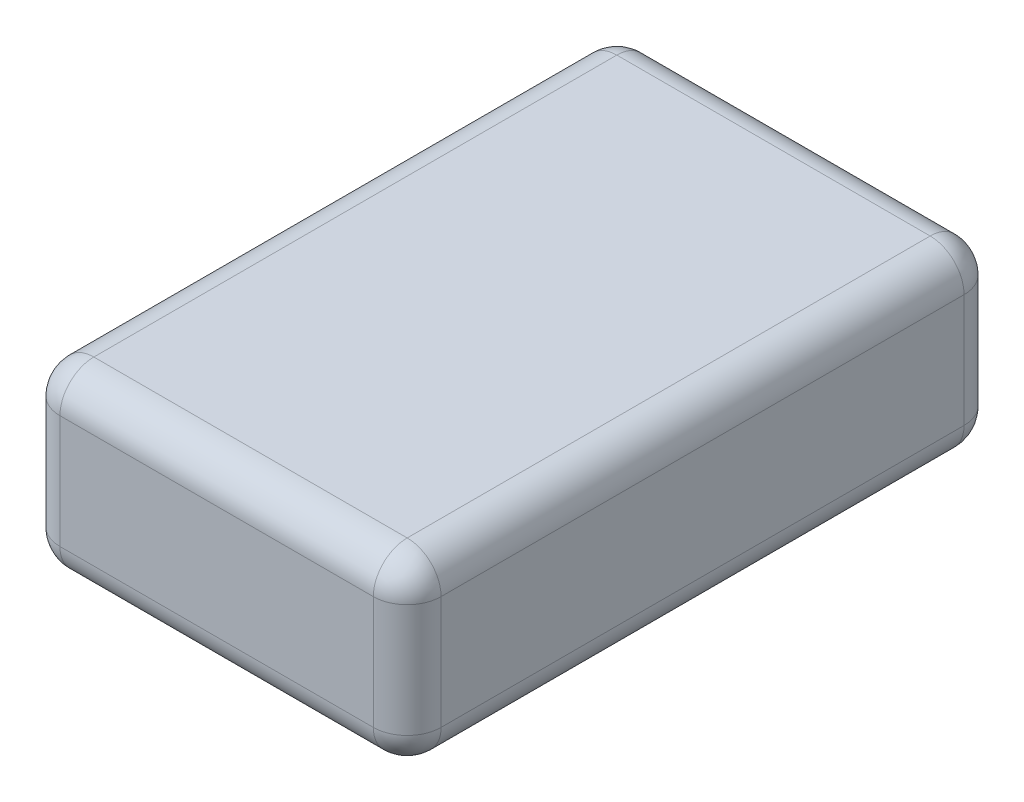
SolidWorks part; units mm, degrees
ref_plane "Front Plane" through (0, 0, 0) normal (0, 0, 1) x (1, 0, 0)
ref_plane "Top Plane" through (0, 0, 0) normal (0, 1, 0) x (1, 0, 0)
ref_plane "Right Plane" through (0, 0, 0) normal (1, 0, 0) x (0, 0, -1)
sketch "Sketch1" plane through (0, 0, 0) normal (0, 1, 0) x (1, 0, 0)
  line L1 (-10, 15.5) -> (10, 15.5)
  line L2 (-10, 15.5) -> (-10, -15.5)
  line L3 (-10, -15.5) -> (10, -15.5)
  line L4 (10, 15.5) -> (10, -15.5)
  line L5 (-10, 15.5) -> (10, -15.5) construction
  line L6 (-10, -15.5) -> (10, 15.5) construction
  point P0 (0, 0)
  dimension "D1" = 31
  dimension "D2" = 20
extrude "Boss-Extrude1" add sketch "Sketch1" along normal mid plane 9.5
fillet "Fillet1" radius 1.778 12 edges at (-10, 0, 15.5) (0, 4.75, 15.5) (-10, 4.75, 0) (10, 0, 15.5) (10, 4.75, 0) (10, 0, -15.5) (0, 4.75, -15.5) (-10, 0, -15.5) (0, -4.75, -15.5) (-10, -4.75, 0) (0, -4.75, 15.5) (10, -4.75, 0)
